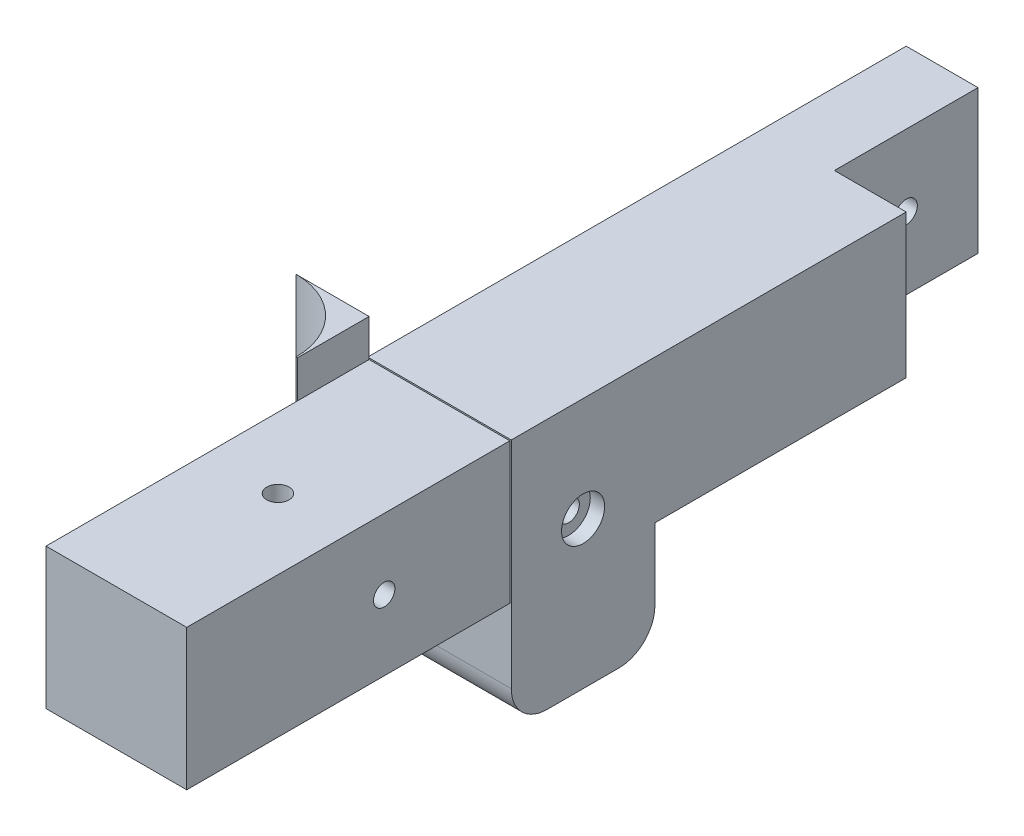
SolidWorks part; units mm, degrees
ref_plane "前视基准面" through (0, 0, 0) normal (0, 0, 1) x (1, 0, 0)
ref_plane "上视基准面" through (0, 0, 0) normal (0, 1, 0) x (1, 0, 0)
ref_plane "右视基准面" through (0, 0, 0) normal (1, 0, 0) x (0, 0, -1)
other "Configuration Table"
sketch "草图1" plane through (0, 0, 0) normal (0, 0, 1) x (1, 0, 0)
  line L1 (0, 0) -> (20, 0)
  line L2 (0, 0) -> (0, 20)
  line L3 (0, 20) -> (20, 20)
  line L4 (20, 0) -> (20, 20)
extrude "凸台-拉伸1" add sketch "草图1" along normal blind 120 contours L2 L1 L4 L3
sketch "草图2" plane through (0, 20, 0) normal (0, 1, 0) x (1, 0, 0)
  line L1 (20, 0) -> (10, 0)
  line L2 (20, 0) -> (20, -20)
  line L3 (20, -20) -> (10, -20)
  line L4 (10, 0) -> (10, -20)
extrude "切除-拉伸1" cut sketch "草图2" against normal blind 120
sketch "草图3" plane through (10, 0, 0) normal (1, 0, 0) x (0, 0, -1)
  line L0 (-20, 20) -> (0, 0)
  circle A0 centre (-10, 10) radius 1.55
extrude "切除-拉伸2" cut sketch "草图3" against normal blind 120 contours L0 A0 | L0 A0
sketch "草图4" plane through (0, 0, 0) normal (-1, 0, 0) x (0, 0, 1)
  circle A0 centre (10, 10) radius 3
extrude "切除-拉伸3" cut sketch "草图4" against normal blind 2
sketch "草图6" plane through (0, 0, 0) normal (-1, 0, 0) x (0, 0, 1)
  line L0 (120, 20) -> (75, 20)
  line L1 (120, 20) -> (0, 20) construction
  line L2 (75, 20) -> (75, 0)
  line L3 (75, 10) -> (92.5, 10)
  circle A0 centre (92.5, 10) radius 1.49
extrude "切除-拉伸4" cut sketch "草图6" against normal blind 20
sketch "草图7" plane through (0, 0, 0) normal (0, -1, 0) x (1, 0, 0)
  line L0 (0, 120) -> (20, 75)
  circle A0 centre (10, 97.5) radius 1.55
extrude "切除-拉伸5" cut sketch "草图7" against normal blind 20 contours L0 A0 | L0 A0
sketch "草图8" plane through (0, 0, 120) normal (0, 0, 1) x (1, 0, 0)
  line L0 (0, 20) -> (0.2, 20)
  line L1 (0, 20) -> (20, 20) construction
  line L2 (0, 20) -> (0, 19.8)
  line L3 (0, 0) -> (0, 20) construction
  line L4 (0, 19.8) -> (20, 19.8)
  line L5 (20, 0) -> (20, 20) construction
  line L6 (0.2, 20) -> (0.2, 19.8)
  line L7 (0.2, 19.8) -> (0.2, 0)
  line L8 (0, 0) -> (20, 0) construction
  line L9 (0.2, 0) -> (0, 0)
  line L10 (0, 0) -> (0, 0.2)
  line L11 (0, 0.2) -> (20, 0.2)
  line L12 (20, 0.2) -> (20, 0)
  line L13 (20, 0) -> (19.8, 0)
  line L14 (19.8, 0) -> (19.8, 20)
  line L15 (19.8, 20) -> (20, 20)
  line L16 (20, 20) -> (20, 0.2)
  line L17 (19.8, 0) -> (0.2, 0)
  line L18 (0.2, 0) -> (19.8, 0)
  line L19 (0, 0.2) -> (0.2, 0.2)
  line L20 (0.2, 0.2) -> (0.2, 0)
  line L21 (0, 0.2) -> (0, 19.8)
  line L22 (0.2, 20) -> (19.8, 20)
  line L23 (19.8, 20) -> (19.8, 19.8)
  line L24 (19.8, 19.8) -> (20, 19.8)
  line M5 (20, 20) -> (0, 20)
  line M6 (0, 20) -> (0, 0)
  line M7 (0, 0) -> (20, 0)
  line M8 (20, 0) -> (20, 20)
extrude "切除-拉伸6" cut sketch "草图8" against normal blind 45 contours L4 L14 L6 M5 | L6 L4 M5 M6 | L11 L7 L4 M6 | L14 L11 L4 M8 | L14 L11 M7 M8 | L14 L11 L7 M7 | L11 L7 M6 M7 | L14 L4 M8 M5
sketch "草图9" plane through (0, 19.8, 0) normal (0, 1, 0) x (1, 0, 0)
  line L1 (0, -75) -> (-10, -75)
  line L2 (0, -85) -> (0.2, -85)
  line L3 (0.2, -75) -> (0.2, -120) construction
  line L4 (0.2, -85) -> (0.2, -75)
  line L5 (0, -75) -> (0.2, -75)
  arc A0 (0, -85) -> (-10, -75) centre (-10, -85) ccw
extrude "凸台-拉伸2" add sketch "草图9" against normal blind 24.8 contours L1 A0 L2 L4 L5
sketch "草图10" plane through (0, 19.8, 0) normal (0, 1, 0) x (1, 0, 0)
  line L0 (-10, -75) -> (0, -75)
  line L3 (0, -85) -> (0.2, -85)
  line L4 (0.2, -85) -> (0.2, -75)
  line L5 (0, -75) -> (19.8, -75) construction
  line L6 (0.2, -75) -> (0, -75)
  arc A0 (0, -85) -> (-10, -75) centre (-10, -85) ccw
  arc A1 (0, -85) -> (-10, -75) centre (-10, -85) ccw construction
extrude "凸台-拉伸3" add sketch "草图10" along normal blind 5.2 contours A0 L3 L4 L6 L0
sketch "草图12" plane through (0, 0, 0) normal (0, -1, 0) x (1, 0, 0)
  line L0 (20, 75) -> (20, 20) construction
  line L1 (0, 75) -> (20, 75)
  line L2 (0, 75) -> (0, 55)
  line L3 (0, 55) -> (20, 55)
  line L4 (20, 75) -> (20, 55)
extrude "凸台-拉伸4" add sketch "草图12" along normal blind 15 contours L2 L1 L4 L3
sketch "草图13" plane through (0, 0, 0) normal (-1, 0, 0) x (0, 0, 1)
  line L0 (55, 0) -> (75, 0)
  line L1 (75, -5) -> (75, 25) construction
  line L2 (65, 0) -> (65, -5)
  line L3 (65, -5) -> (60, -5)
  line L4 (65, -5) -> (70, -5)
  line L5 (65, -5) -> (65, -9.5)
  line L6 (65, -9.5) -> (60, -9.5)
  line L7 (65, -9.5) -> (70, -9.5)
  line L8 (60, -9.5) -> (60, -5)
  line L9 (70, -9.5) -> (70, -5)
  line L10 (60, -5) -> (60, 10.5)
  line L11 (70, -5) -> (70, 10.5)
  line L12 (60, 10.5) -> (70, 10.5)
extrude "切除-拉伸8" cut sketch "草图13" against normal blind 15 contours L12 L10 L0 L11 | L10 L3 L2 L0 | L4 L11 L0 L2 | L8 L6 L5 L3 | L7 L9 L4 L5
sketch "草图14" plane through (0, 0, 0) normal (0, 0, -1) x (-1, 0, 0)
  line L0 (-10, 20) -> (0, 0)
  line L1 (-5, 10) -> (-5, 14)
  circle A0 centre (-5, 14) radius 2
extrude "切除-拉伸9" cut sketch "草图14" against normal blind 70
sketch "草图15" plane through (0, 0, 0) normal (-1, 0, 0) x (0, 0, 1)
  line L5 (60, 10.5) -> (70, 10.5)
  line L6 (60, 10.5) -> (60, 16)
  line L7 (60, 16) -> (70, 16)
  line L8 (70, 10.5) -> (70, 16)
extrude "切除-拉伸10" cut sketch "草图15" against normal blind 15
sketch "草图16" plane through (15, 0, 0) normal (-1, 0, 0) x (0, 0, 1)
  line L0 (60, -9.5) -> (60, 5.5)
  line L1 (60, -9.5) -> (60, 16) construction
  line L2 (60, 5.5) -> (65, 5.5)
  line L3 (65, 5.5) -> (65, -5)
  circle A0 centre (65, 5.5) radius 1.48
extrude "切除-拉伸11" cut sketch "草图16" against normal blind 5 contours L3 A0 L2 | L2 A0 L3
sketch "草图17" plane through (0, 0, 0) normal (-1, 0, 0) x (0, 0, 1)
  line L0 (55, -15) -> (55, -10)
  line L1 (55, -15) -> (55, 0) construction
  line L2 (55, -10) -> (60, -10)
  line L3 (75, -15) -> (75, -10)
  line L4 (75, -15) -> (75, -5) construction
  line L5 (75, -10) -> (70, -10)
  line L6 (75, -15) -> (55, -15) construction
  line L7 (55, -15) -> (60, -15)
  line L8 (70, -15) -> (75, -15)
  arc A0 (55, -10) -> (60, -15) centre (60, -10) ccw
  arc A1 (70, -15) -> (75, -10) centre (70, -10) ccw
  line M10 (55, 0) -> (55, -15)
  line M11 (55, -15) -> (75, -15)
  line M12 (75, -15) -> (75, -5)
extrude "切除-拉伸12" cut sketch "草图17" against normal blind 20 contours A0 M10 M11 | A1 M11 M12
sketch "草图18" plane through (20, 0, 0) normal (1, 0, 0) x (0, 0, -1)
  circle A0 centre (-65, 5.5) radius 3
extrude "切除-拉伸13" cut sketch "草图18" against normal blind 2
sketch "草图19" plane through (0, 0, 0) normal (-1, 0, 0) x (0, 0, 1)
  line L1 (70, 16) -> (70.2, 16)
  line L2 (70, 16) -> (70, -9.5)
  line L3 (70, -9.5) -> (70.2, -9.5)
  line L4 (70.2, 16) -> (70.2, -9.5)
  line L5 (60, 16) -> (59.8, 16)
  line L6 (60, 16) -> (60, -9.5)
  line L7 (60, -9.5) -> (59.8, -9.5)
  line L8 (59.8, 16) -> (59.8, -9.5)
extrude "切除-拉伸14" cut sketch "草图19" against normal blind 15 contours L2 L1 L4 L3 | L6 L5 L8 L7
sketch "草图21" plane through (0, 0, 0) normal (-1, 0, 0) x (0, 0, 1)
  line L1 (59.8, -9.5) -> (70.2, -9.5)
  line L2 (59.8, -9.5) -> (59.8, -9.7)
  line L3 (59.8, -9.7) -> (70.2, -9.7)
  line L4 (70.2, -9.5) -> (70.2, -9.7)
extrude "切除-拉伸15" cut sketch "草图21" against normal blind 15
